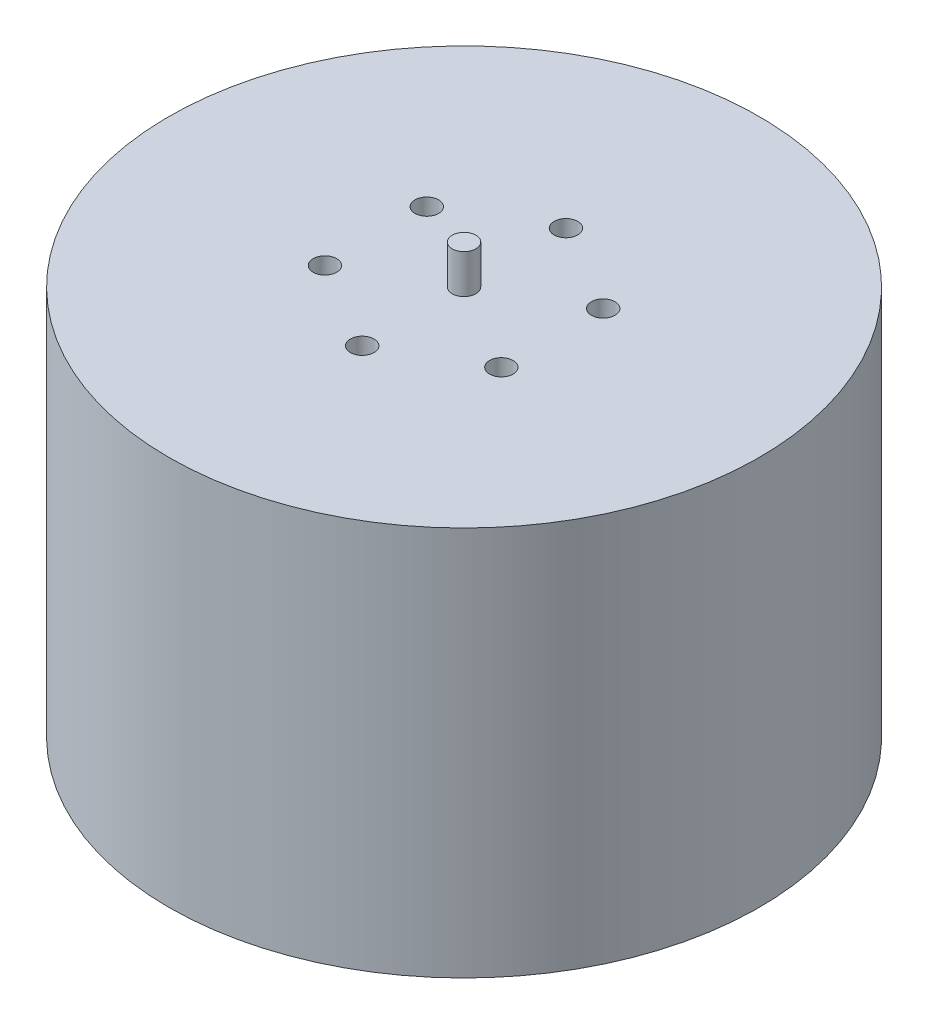
SolidWorks part; units mm, degrees
ref_plane "前视基准面" through (0, 0, 0) normal (0, 0, 1) x (1, 0, 0)
ref_plane "上视基准面" through (0, 0, 0) normal (0, 1, 0) x (1, 0, 0)
ref_plane "右视基准面" through (0, 0, 0) normal (1, 0, 0) x (0, 0, -1)
sketch "草图1" plane through (0, 0, 0) normal (0, 1, 0) x (1, 0, 0)
  circle A0 centre (0, 0) radius 50
extrude "凸台-拉伸1" add sketch "草图1" along normal blind 66
sketch "草图2" plane through (0, 66, 0) normal (0, 1, 0) x (1, 0, 0)
  circle A0 centre (0, 0) radius 17.25
  circle A1 centre (0, 17.25) radius 2
  circle A2 centre (14.9389, 8.625) radius 2
  circle A3 centre (14.9389, -8.625) radius 2
  circle A4 centre (0, -17.25) radius 2
  circle A5 centre (-14.9389, -8.625) radius 2
  circle A6 centre (-14.9389, 8.625) radius 2
  circle A7 centre (0, 0) radius 2
  point P17 (0, 0)
  dimension "D1" = 6
extrude "切除-拉伸2" cut sketch "草图2" against normal through all contours A2 | A3 | A4 | A5 | A1 | A6
sketch "草图3" plane through (0, 66, 0) normal (0, 1, 0) x (1, 0, 0)
  circle A0 centre (0, 0) radius 2
extrude "凸台-拉伸2" add sketch "草图3" along normal blind 6.6
sketch "草图4" plane through (0, 0, 0) normal (0, -1, 0) x (-1, 0, 0)
  circle A0 centre (0, 0) radius 3
extrude "切除-拉伸3" cut sketch "草图4" against normal blind 6
sketch "草图7" plane through (0, 6, 0) normal (0, -1, 0) x (-1, 0, 0)
  circle A0 centre (0, 0) radius 33 construction
  dimension "D1" = 66
sketch "草图8" plane through (0, 0, 0) normal (0, -1, 0) x (-1, 0, 0)
  line L0 (0, 32.2229) -> (0, -33.9047) construction
  circle A0 centre (0, 32.2229) radius 2
  circle A1 centre (32.2229, 0) radius 2
  circle A2 centre (0, -32.2229) radius 2
  circle A3 centre (-32.2229, 0) radius 2
  point P13 (0, 0)
  dimension "D1" = 4
extrude "切除-拉伸4" cut sketch "草图8" against normal blind 6
